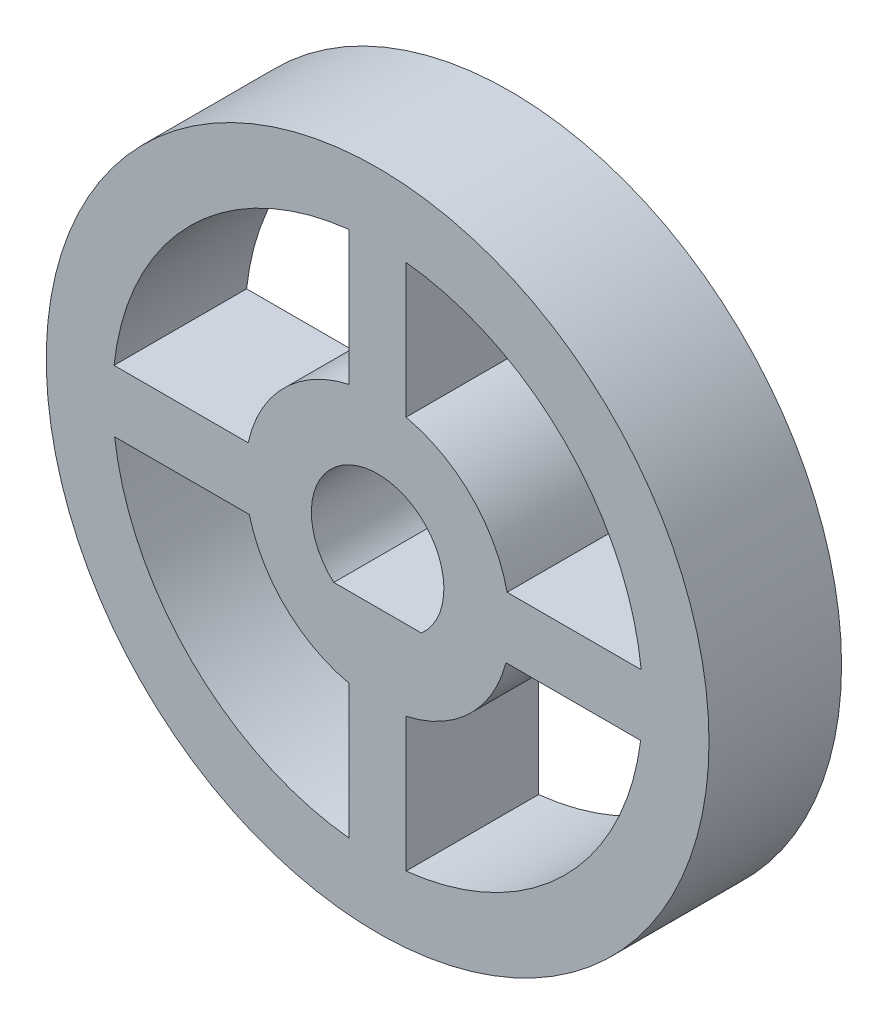
SolidWorks part; units mm, degrees
ref_plane "Front Plane" through (0, 0, 0) normal (0, 0, 1) x (1, 0, 0)
ref_plane "Top Plane" through (0, 0, 0) normal (0, 1, 0) x (1, 0, 0)
ref_plane "Right Plane" through (0, 0, 0) normal (1, 0, 0) x (0, 0, -1)
sketch "Sketch1" plane through (0, 0, 0) normal (0, 0, 1) x (1, 0, 0)
  line L0 (-1.2857, 5.8606) -> (-1.2857, 11.9309)
  line L1 (1.2857, 5.8606) -> (1.2857, 11.9309)
  line L2 (5.8606, 1.2857) -> (11.9309, 1.2857)
  line L8 (-1.2857, -11.9309) -> (-1.2857, -5.8606)
  line L10 (1.2857, -11.9309) -> (1.2857, -5.8606)
  line L11 (5.8095, -1.5) -> (11.9059, -1.5)
  line L13 (-11.9059, -1.5) -> (-5.8095, -1.5)
  line L15 (-11.9309, 1.2857) -> (-5.8606, 1.2857)
  line L20 (0, 3) -> (0, -2.25) construction
  line L21 (-1.9843, -2.25) -> (1.9843, -2.25)
  circle A0 centre (0, 0) radius 15
  arc A1 (1.9843, -2.25) -> (-1.9843, -2.25) centre (0, 0) ccw
  arc A2 (-5.8095, -1.5) -> (-1.2857, -5.8606) centre (0, 0) ccw
  arc A3 (-11.9059, -1.5) -> (-1.2857, -11.9309) centre (0, 0) ccw
  arc A4 (-1.2857, 5.8606) -> (-5.8606, 1.2857) centre (0, 0) ccw
  arc A5 (-1.2857, 11.9309) -> (-11.9309, 1.2857) centre (0, 0) ccw
  arc A6 (5.8606, 1.2857) -> (1.2857, 5.8606) centre (0, 0) ccw
  arc A7 (11.9309, 1.2857) -> (1.2857, 11.9309) centre (0, 0) ccw
  arc A8 (1.2857, -11.9309) -> (11.9059, -1.5) centre (0, 0) ccw
  arc A9 (1.2857, -5.8606) -> (5.8095, -1.5) centre (0, 0) ccw
  dimension "D1" = 30
  dimension "D2" = 6
  dimension "D3" = 3
  dimension "D4" = 3
  dimension "D5" = 23.8118
  dimension "D6" = 3.9686
extrude "Boss-Extrude1" add sketch "Sketch1" along normal blind 6
